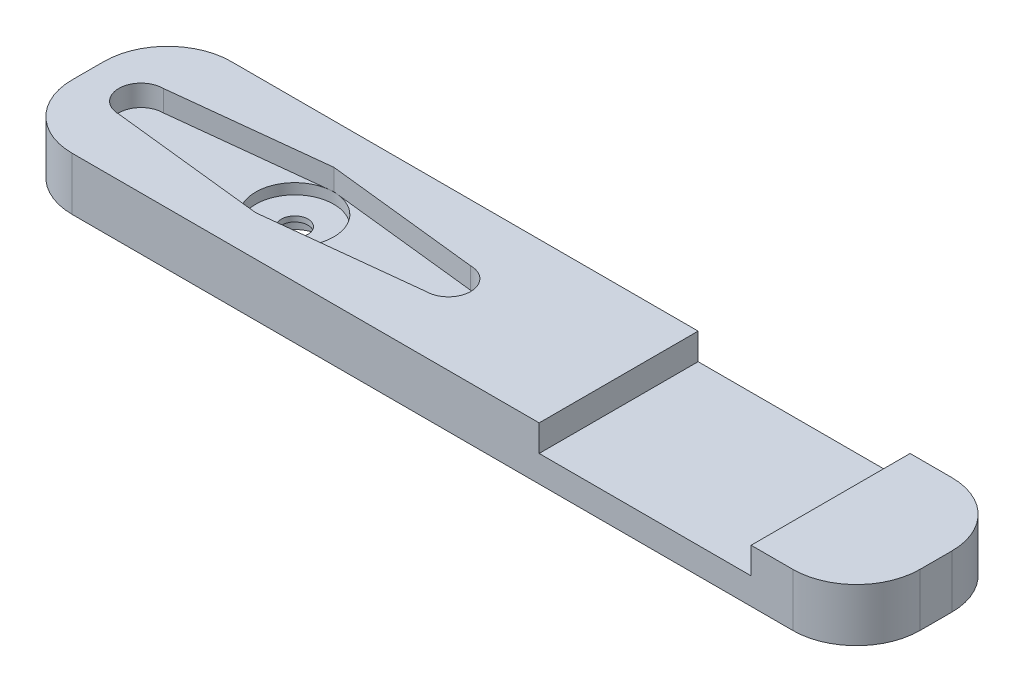
SolidWorks part; units mm, degrees
ref_plane "Front Plane" through (0, 0, 0) normal (0, 0, 1) x (1, 0, 0)
ref_plane "Top Plane" through (0, 0, 0) normal (0, 1, 0) x (1, 0, 0)
ref_plane "Right Plane" through (0, 0, 0) normal (1, 0, 0) x (0, 0, -1)
sketch "Sketch1" plane through (0, 0, 0) normal (0, 1, 0) x (1, 0, 0)
  line L1 (40, -7.5) -> (-40, -7.5)
  line L2 (40, -7.5) -> (40, 7.5)
  line L3 (40, 7.5) -> (-40, 7.5)
  line L4 (-40, -7.5) -> (-40, 7.5)
  line L5 (40, -7.5) -> (-40, 7.5) construction
  line L6 (40, 7.5) -> (-40, -7.5) construction
  point P0 (0, 0)
  dimension "D1" = 80
  dimension "D2" = 15
extrude "Boss-Extrude1" add sketch "Sketch1" along normal blind 5
fillet "Fillet1" radius 6 4 edges at (40, 2.5, 7.5) (40, 2.5, -7.5) (-40, 2.5, 7.5) (-40, 2.5, -7.5)
sketch "Sketch3" plane through (0, 5, 0) normal (0, 1, 0) x (1, 0, 0)
  line L0 (34, 7.5) -> (-34, 7.5) construction
  line L1 (10.0625, 7.5) -> (30.0625, 7.5)
  line L2 (10.0625, 7.5) -> (10.0625, -7.5)
  line L3 (10.0625, -7.5) -> (30.0625, -7.5)
  line L4 (30.0625, 7.5) -> (30.0625, -7.5)
  line L5 (-34, -7.5) -> (34, -7.5) construction
  dimension "D1" = 20
extrude "Cut-Extrude2" cut sketch "Sketch3" against normal blind 2.5
sketch "Sketch4" plane through (0, 5, 0) normal (0, 1, 0) x (1, 0, 0)
  line L0 (0, 0) -> (-55.781, 0) construction
  line L1 (-20.5, 3.7) -> (-6, 2.1)
  line L2 (-20.5, -3.7) -> (-6, -2.1)
  line L3 (-20.5, 0) -> (-20.5, 15.155) construction
  line L4 (-20.5, -3.7) -> (-35, -2.1)
  line L5 (-20.5, 3.7) -> (-35, 2.1)
  arc A0 (-21.3067, -3.611) -> (-19.6933, -3.611) centre (-20.5, 0) ccw
  arc A1 (-6, -2.1) -> (-6, 2.1) centre (-6, 0) ccw
  arc A2 (-35, -2.1) -> (-35, 2.1) centre (-35, 0) cw
  arc A3 (-19.6933, 3.611) -> (-21.3067, 3.611) centre (-20.5, 0) ccw
  dimension "D1" = 7.4
  dimension "D2" = 4.2
  dimension "D3" = 14.5
  dimension "D4" = 6
extrude "Cut-Extrude3" cut sketch "Sketch4" against normal blind 2 contours L5 A2 L4 L2 A1 L1
sketch "Sketch5" plane through (0, 3, 0) normal (0, 1, 0) x (1, 0, 0)
  line L0 (-20.5, 3.7) -> (-20.5, -12.8184) construction
  circle A0 centre (-20.5, 0) radius 1.25
  dimension "D1" = 2.5
extrude "Cut-Extrude4" cut sketch "Sketch5" against normal through all
sketch "Sketch6" plane through (0, 0, 0) normal (0, -1, 0) x (-1, 0, 0)
  circle A0 centre (20.5, 0) radius 2.5
  dimension "D1" = 5
extrude "Cut-Extrude5" cut sketch "Sketch6" against normal blind 1.5
sketch "Sketch7" plane through (0, 3, 0) normal (0, 1, 0) x (1, 0, 0)
  circle A0 centre (-20.5, 0) radius 3.6777
extrude "Cut-Extrude6" cut sketch "Sketch7" against normal blind 1
